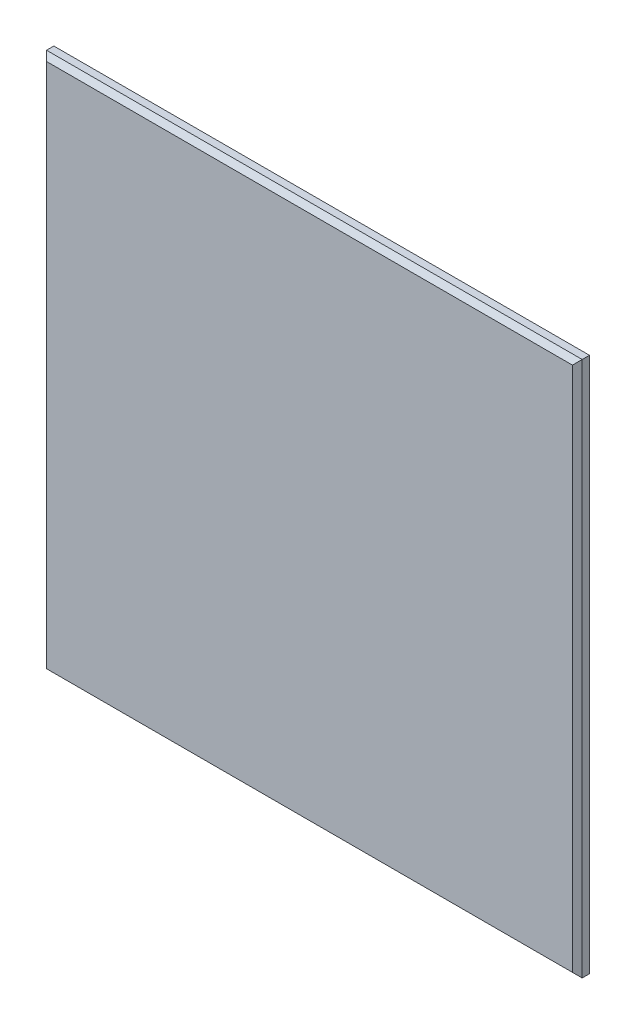
SolidWorks part; units mm, degrees
ref_plane "Front Plane" through (0, 0, 0) normal (0, 0, 1) x (1, 0, 0)
ref_plane "Top Plane" through (0, 0, 0) normal (0, 1, 0) x (1, 0, 0)
ref_plane "Right Plane" through (0, 0, 0) normal (1, 0, 0) x (0, 0, -1)
sketch "Sketch1" plane through (0, 0, 0) normal (0, 0, 1) x (1, 0, 0)
  line L1 (-110, 110) -> (110, 110)
  line L2 (-110, 110) -> (-110, -110)
  line L3 (-110, -110) -> (110, -110)
  line L4 (110, 110) -> (110, -110)
  line L5 (-110, 110) -> (110, -110) construction
  line L6 (-110, -110) -> (110, 110) construction
  point P0 (0, 0)
extrude "Boss-Extrude1" add sketch "Sketch1" along normal blind 5
chamfer "Chamfer1" distance 2 angle 45 4 edges at (0, 110, 5) (-110, 0, 5) (0, -110, 5) (110, 0, 5)
